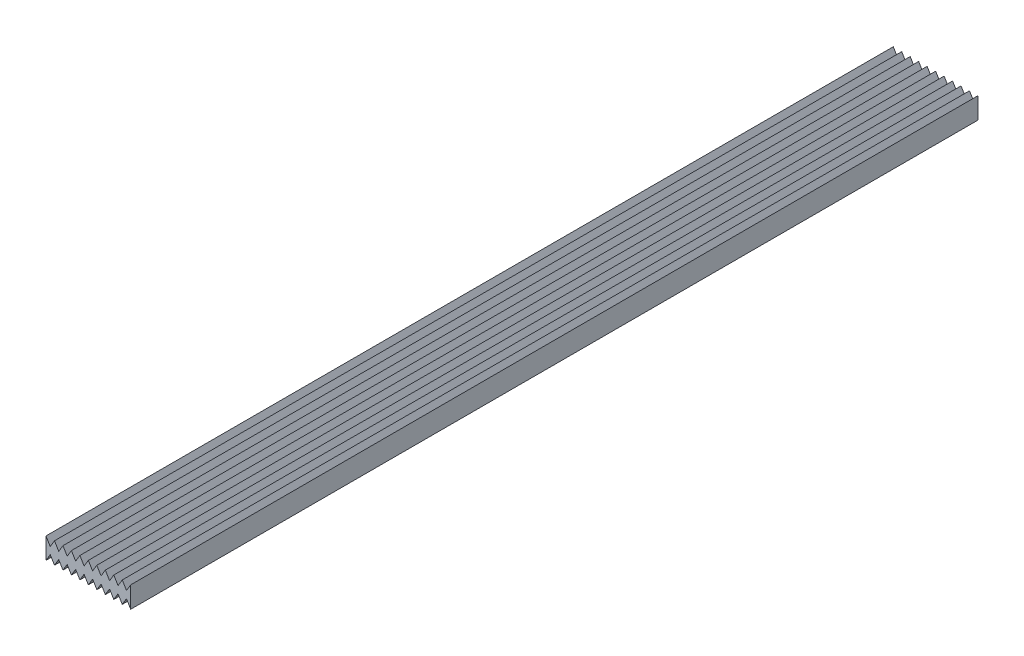
SolidWorks part; units mm, degrees
ref_plane "Front Plane" through (0, 0, 0) normal (0, 0, 1) x (1, 0, 0)
ref_plane "Top Plane" through (0, 0, 0) normal (0, 1, 0) x (1, 0, 0)
ref_plane "Right Plane" through (0, 0, 0) normal (1, 0, 0) x (0, 0, -1)
sketch "Sketch1" plane through (0, 0, 0) normal (0, 0, 1) x (1, 0, 0)
  line L0 (-30, 7.5) -> (-27, 2.5)
  line L1 (30, 7.5) -> (-30, 7.5)
  line L2 (30, 7.5) -> (30, -7.5)
  line L3 (30, -7.5) -> (-30, -7.5)
  line L4 (-30, 7.5) -> (-30, -7.5)
  line L5 (30, 7.5) -> (-30, -7.5) construction
  line L6 (30, -7.5) -> (-30, 7.5) construction
  line L7 (-27, 2.5) -> (-24, 7.5)
  line L8 (-27, 7.5) -> (-27, -7.5) construction
  line L9 (-30, 0) -> (30, 0) construction
  line L10 (-24, 7.5) -> (-21, 2.5)
  line L11 (-21, 2.5) -> (-18, 7.5)
  line L12 (-18, 7.5) -> (-15, 2.5)
  line L13 (-15, 2.5) -> (-12, 7.5)
  line L14 (-12, 7.5) -> (-9, 2.5)
  line L15 (-9, 2.5) -> (-6, 7.5)
  line L16 (-6, 7.5) -> (-3, 2.5)
  line L17 (-3, 2.5) -> (0, 7.5)
  line L18 (0, 7.5) -> (3, 2.5)
  line L19 (3, 2.5) -> (6, 7.5)
  line L20 (6, 7.5) -> (9, 2.5)
  line L21 (9, 2.5) -> (12, 7.5)
  line L22 (12, 7.5) -> (15, 2.5)
  line L23 (15, 2.5) -> (18, 7.5)
  line L24 (18, 7.5) -> (21, 2.5)
  line L25 (21, 2.5) -> (24, 7.5)
  line L26 (24, 7.5) -> (27, 2.5)
  line L27 (27, 2.5) -> (30, 7.5)
  line L28 (27, -2.5) -> (30, -7.5)
  line L29 (24, -7.5) -> (27, -2.5)
  line L30 (21, -2.5) -> (24, -7.5)
  line L31 (18, -7.5) -> (21, -2.5)
  line L32 (15, -2.5) -> (18, -7.5)
  line L33 (12, -7.5) -> (15, -2.5)
  line L34 (9, -2.5) -> (12, -7.5)
  line L35 (6, -7.5) -> (9, -2.5)
  line L36 (3, -2.5) -> (6, -7.5)
  line L37 (0, -7.5) -> (3, -2.5)
  line L38 (-3, -2.5) -> (0, -7.5)
  line L39 (-6, -7.5) -> (-3, -2.5)
  line L40 (-9, -2.5) -> (-6, -7.5)
  line L41 (-12, -7.5) -> (-9, -2.5)
  line L42 (-15, -2.5) -> (-12, -7.5)
  line L43 (-18, -7.5) -> (-15, -2.5)
  line L44 (-21, -2.5) -> (-18, -7.5)
  line L45 (-24, -7.5) -> (-21, -2.5)
  line L46 (-27, -2.5) -> (-24, -7.5)
  line L47 (-30, -7.5) -> (-27, -2.5)
  point P0 (0, 0)
  dimension "D1" = 15
  dimension "D2" = 60
  dimension "D4" = 5
  dimension "D5" = 10
extrude "Boss-Extrude1" add sketch "Sketch1" along normal mid plane 600 contours L4 L47 L46 L45 L44 L43 L42 L41 L40 L39 L38 L37 L36 L35 L34 L33 L32 L31 L30 L29 L28 L2 L27 L26 L25 L24 L23 L22 L21 L20 L19 L18 L17 L16 L15 L14 L13 L12 L11 L10 L7 L0
